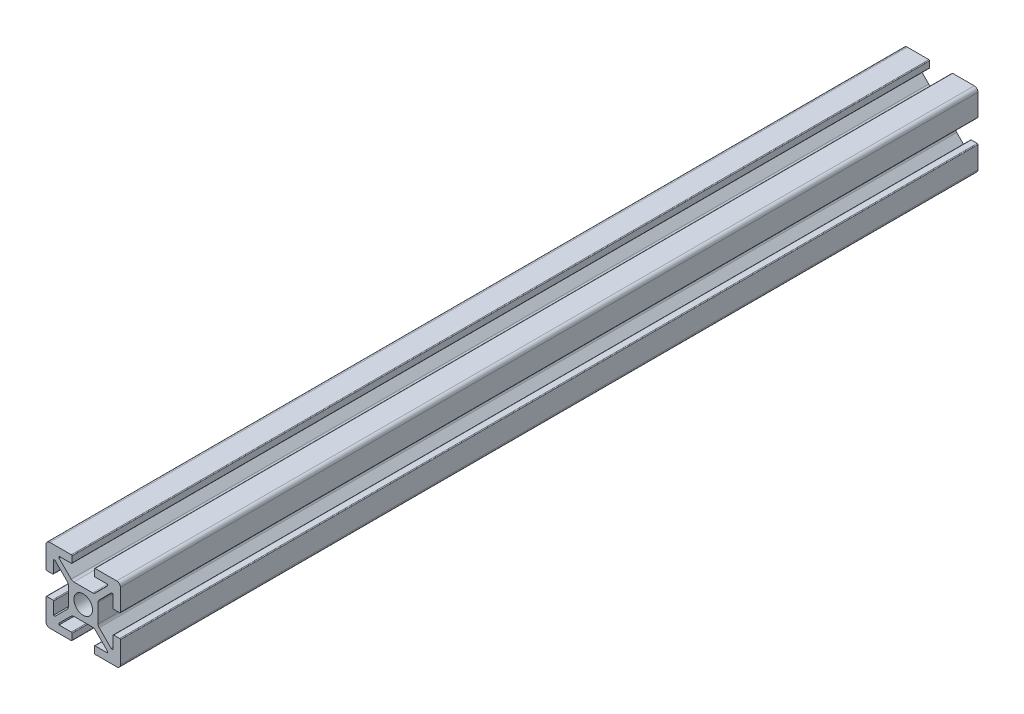
SolidWorks part; units mm, degrees
ref_plane "Front Plane" through (0, 0, 0) normal (0, 0, 1) x (1, 0, 0)
ref_plane "Top Plane" through (0, 0, 0) normal (0, 1, 0) x (1, 0, 0)
ref_plane "Right Plane" through (0, 0, 0) normal (1, 0, 0) x (0, 0, -1)
sketch "Sketch1" plane through (0, 0, 0) normal (0, 0, 1) x (1, 0, 0)
  line L0 (0.2, 13) -> (1.8, 13)
  line L1 (13.2, 0) -> (19, 0)
  line L2 (0, 13.2) -> (0, 19)
  line L3 (1, 20) -> (6.8, 20)
  line L4 (20, 1) -> (20, 6.8)
  line L5 (2, 13.2) -> (2, 16.5)
  line L6 (2, 16.5) -> (2.4393, 16.5)
  line L7 (2.4393, 16.5) -> (5.7071, 13.2322)
  line L8 (6, 12.5251) -> (6, 7.4749)
  line L11 (7.4749, 14) -> (10, 14)
  line L12 (3.5, 17.5607) -> (6.7678, 14.2929)
  line L13 (3.5, 18) -> (3.5, 17.5607)
  line L14 (6.8, 18) -> (3.5, 18)
  line L15 (6.8, 20) -> (1, 20)
  line L16 (7, 19.8) -> (7, 18.2)
  line L17 (19.8, 7) -> (18.2, 7)
  line L18 (20, 6.8) -> (20, 1)
  line L19 (18, 6.8) -> (18, 3.5)
  line L20 (18, 3.5) -> (17.5607, 3.5)
  line L21 (17.5607, 3.5) -> (14.2929, 6.7678)
  line L22 (14, 7.4749) -> (14, 12.5251)
  line L23 (12.5251, 6) -> (10, 6)
  line L24 (16.5, 2.4393) -> (13.2322, 5.7071)
  line L25 (16.5, 2) -> (16.5, 2.4393)
  line L26 (13.2, 2) -> (16.5, 2)
  line L27 (13.2, 0) -> (19, 0)
  line L28 (13, 0.2) -> (13, 1.8)
  line L30 (13, 19.8) -> (13, 18.2)
  line L31 (13.2, 20) -> (19, 20)
  line L32 (13.2, 18) -> (16.5, 18)
  line L33 (16.5, 18) -> (16.5, 17.5607)
  line L34 (16.5, 17.5607) -> (13.2322, 14.2929)
  line L35 (12.5251, 14) -> (10, 14)
  line L36 (17.5607, 16.5) -> (14.2929, 13.2322)
  line L37 (18, 16.5) -> (17.5607, 16.5)
  line L38 (18, 13.2) -> (18, 16.5)
  line L39 (20, 13.2) -> (20, 19)
  line L40 (19.8, 13) -> (18.2, 13)
  line L41 (7, 0.2) -> (7, 1.8)
  line L42 (6.8, 0) -> (1, 0)
  line L43 (6.8, 2) -> (3.5, 2)
  line L44 (3.5, 2) -> (3.5, 2.4393)
  line L45 (3.5, 2.4393) -> (6.7678, 5.7071)
  line L46 (7.4749, 6) -> (10, 6)
  line L47 (2.4393, 3.5) -> (5.7071, 6.7678)
  line L48 (2, 3.5) -> (2.4393, 3.5)
  line L49 (2, 6.8) -> (2, 3.5)
  line L50 (20, 19) -> (20, 13.2)
  line L51 (1, 0) -> (6.8, 0)
  line L52 (0, 6.8) -> (0, 1)
  line L53 (13.2, 20) -> (19, 20)
  line L54 (0.2, 7) -> (1.8, 7)
  arc A0 (20, 1) -> (19, 0) centre (19, 1) cw
  arc A1 (1, 0) -> (0, 1) centre (1, 1) cw
  arc A2 (0, 19) -> (1, 20) centre (1, 19) cw
  arc A3 (20, 19) -> (19, 20) centre (19, 19) ccw
  arc A4 (14.2929, 6.7678) -> (14, 7.4749) centre (15, 7.4749) cw
  arc A5 (12.5251, 6) -> (13.2322, 5.7071) centre (12.5251, 5) cw
  arc A6 (6.7678, 5.7071) -> (7.4749, 6) centre (7.4749, 5) cw
  arc A7 (5.7071, 6.7678) -> (6, 7.4749) centre (5, 7.4749) ccw
  arc A8 (14.2929, 13.2322) -> (14, 12.5251) centre (15, 12.5251) ccw
  arc A9 (13.2322, 14.2929) -> (12.5251, 14) centre (12.5251, 15) cw
  arc A10 (6, 12.5251) -> (5.7071, 13.2322) centre (5, 12.5251) ccw
  arc A11 (7.4749, 14) -> (6.7678, 14.2929) centre (7.4749, 15) cw
  arc A12 (0, 6.8) -> (0.2, 7) centre (0.2, 6.8) cw
  arc A13 (2, 6.8) -> (1.8, 7) centre (1.8, 6.8) ccw
  arc A14 (7, 1.8) -> (6.8, 2) centre (6.8, 1.8) ccw
  arc A15 (7, 0.2) -> (6.8, 0) centre (6.8, 0.2) cw
  arc A16 (13.2, 0) -> (13, 0.2) centre (13.2, 0.2) cw
  arc A17 (13.2, 2) -> (13, 1.8) centre (13.2, 1.8) ccw
  arc A18 (18.2, 7) -> (18, 6.8) centre (18.2, 6.8) ccw
  arc A19 (19.8, 7) -> (20, 6.8) centre (19.8, 6.8) cw
  arc A20 (20, 13.2) -> (19.8, 13) centre (19.8, 13.2) cw
  arc A21 (18, 13.2) -> (18.2, 13) centre (18.2, 13.2) ccw
  arc A22 (13, 19.8) -> (13.2, 20) centre (13.2, 19.8) cw
  arc A23 (13, 18.2) -> (13.2, 18) centre (13.2, 18.2) ccw
  arc A24 (6.8, 18) -> (7, 18.2) centre (6.8, 18.2) ccw
  arc A25 (7, 19.8) -> (6.8, 20) centre (6.8, 19.8) ccw
  arc A26 (1.8, 13) -> (2, 13.2) centre (1.8, 13.2) ccw
  arc A27 (0.2, 13) -> (0, 13.2) centre (0.2, 13.2) cw
  circle A28 centre (10, 10) radius 2.5
  point P19 (2, 13)
  dimension "D1" = 1
  dimension "D4" = 1
  dimension "D5" = 0.2
  dimension "D6" = 0.2
  dimension "D7" = 5
  dimension "D2" = 7
  dimension "D3" = 2
  dimension "D9" = 3.5
extrude "Boss-Extrude1" add sketch "Sketch1" along normal blind 230.5 contours A27 L0 A26 L5 L6 L7 A10 L8 A7 L47 L48 L49 A13 L54 A12 L52 A1 L42 A15 L41 A14 L43 L44 L45 A6 L46 L23 A5 L24 L25 L26 A17 L28 A16 L1 A0 L4 A19 L17 A18 L19 L20 L21 A4 L22 A8 L36 L37 L38 A21 L40
